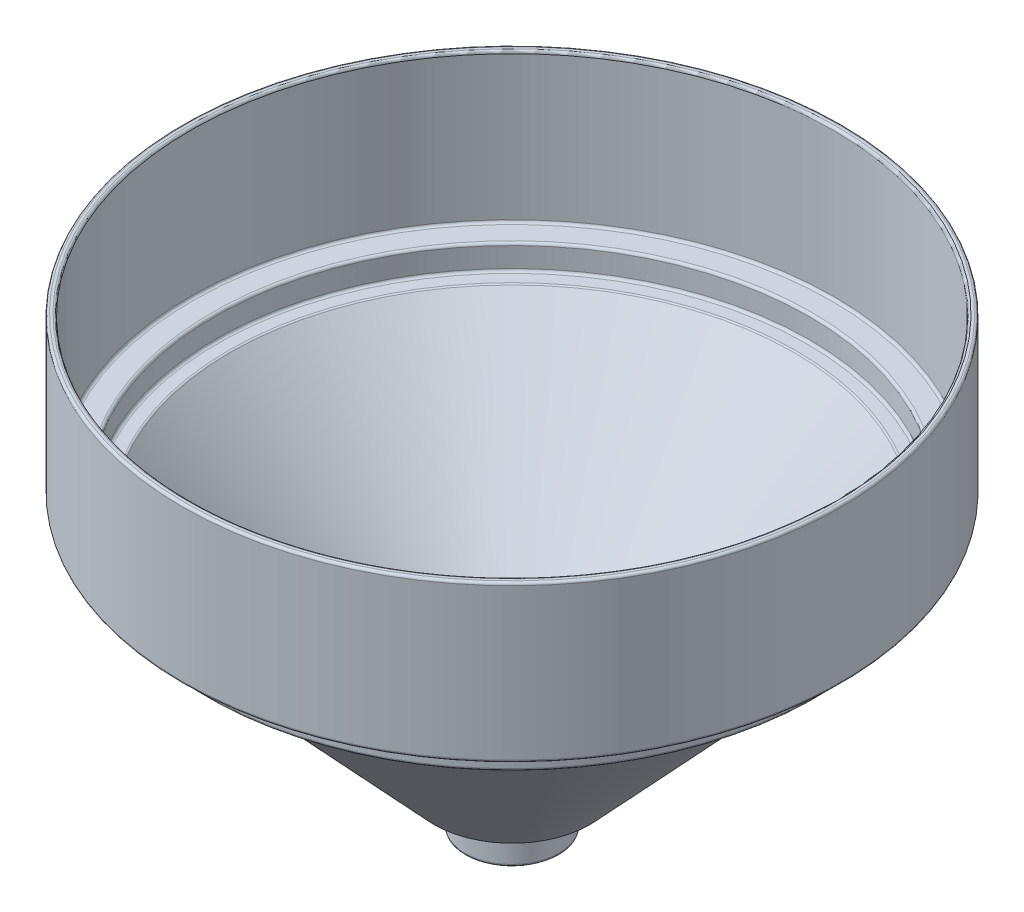
SolidWorks part; units mm, degrees
ref_plane "Front Plane" through (0, 0, 0) normal (0, 0, 1) x (1, 0, 0)
ref_plane "Top Plane" through (0, 0, 0) normal (0, 1, 0) x (1, 0, 0)
ref_plane "Right Plane" through (0, 0, 0) normal (1, 0, 0) x (0, 0, -1)
sketch "Sketch1" plane through (0, 0, 0) normal (1, 0, 0) x (0, 0, -1)
  line L0 (8, 0) -> (8, -10)
  line L1 (8, 0) -> (15, 0)
  line L2 (15, 0) -> (57, 45)
  line L3 (57, 45) -> (60, 45)
  line L4 (60, 45) -> (60, 50)
  line L5 (60, 50) -> (65, 50)
  line L6 (65, 50) -> (65, 80)
  line L7 (0, 0) -> (0, 27.3207) construction
  dimension "D1" = 8
  dimension "D2" = 15
  dimension "D3" = 10
  dimension "D4" = 60
  dimension "D5" = 3
  dimension "D6" = 50
  dimension "D7" = 5
  dimension "D8" = 30
  dimension "D9" = 5
revolve "Revolve-Thin1" add sketch "Sketch1" angle 360 about L7 wall 1.5
fillet "Fillet1" radius 0.5 16 edges at (0, 50, -60) (0, 50, -65) (0, 45, -60) (0, 45, -57) (0, 0, -8) (0, 0, -15) (0, -10, -9.5) (0, -10, -8) (0, -1.5, -9.5) (0, -1.5, -15.6518) (0, 80, -65) (0, 80, -66.5) (0, 43.5, -57.6518) (0, 48.5, -61.5) (0, 43.5, -61.5) (0, 48.5, -66.5)
